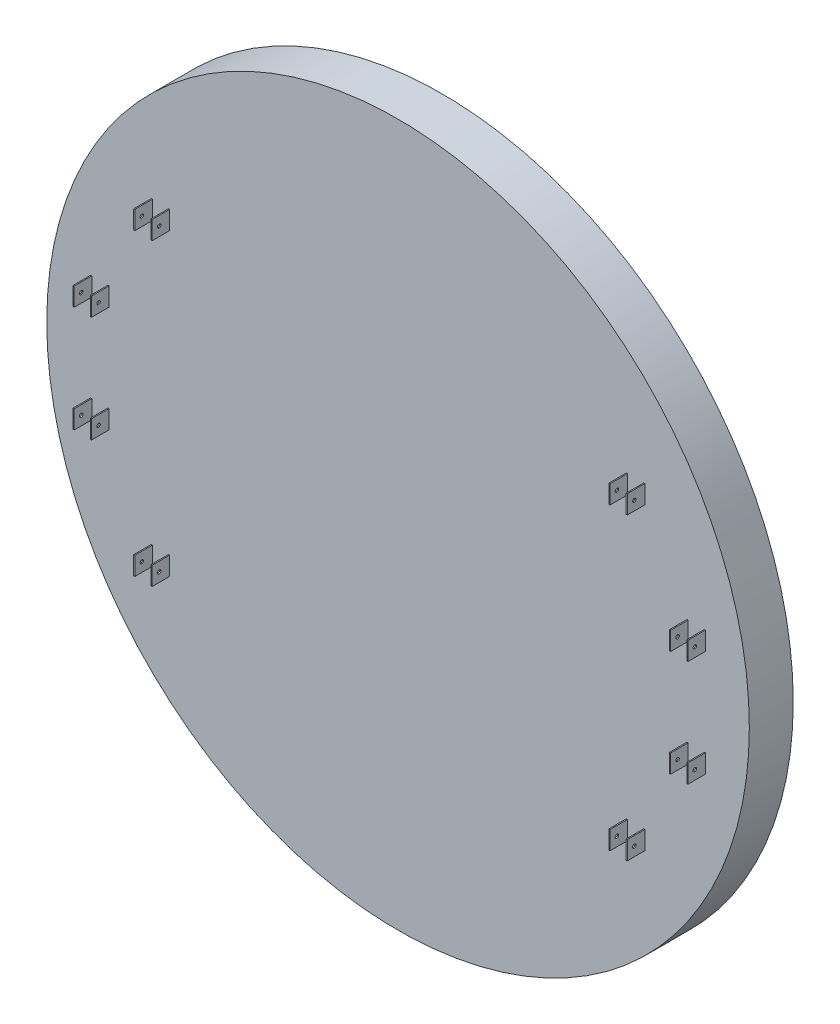
SolidWorks part; units mm, degrees
ref_plane "Front Plane" through (0, 0, 0) normal (0, 0, 1) x (1, 0, 0)
ref_plane "Top Plane" through (0, 0, 0) normal (0, 1, 0) x (1, 0, 0)
ref_plane "Right Plane" through (0, 0, 0) normal (1, 0, 0) x (0, 0, -1)
sketch "Sketch1" plane through (0, 0, 0) normal (0, 0, 1) x (1, 0, 0)
  circle A0 centre (0, 0) radius 400
extrude "Boss-Extrude1" add sketch "Sketch1" along normal blind 50
sketch "Sketch2" plane through (0, 0, 50) normal (0, 0, 1) x (1, 0, 0)
  line L0 (0, 0) -> (400, 0) construction
  line L1 (0, 0) -> (0, 400) construction
  line L2 (350, -50) -> (329, -50)
  line L3 (350, 71) -> (329, 71)
  line L4 (350, 71) -> (350, 50)
  line L5 (350, 50) -> (329, 50)
  line L6 (329, 71) -> (329, 50)
  line L7 (350, -50) -> (350, -71)
  line L8 (329, -50) -> (329, -71)
  line L9 (350, -71) -> (329, -71)
  line L10 (281, -160) -> (281, -181)
  line L11 (281, 160) -> (260, 160)
  line L12 (281, 160) -> (281, 181)
  line L13 (281, 181) -> (260, 181)
  line L14 (260, 160) -> (260, 181)
  line L15 (260, -160) -> (260, -181)
  line L16 (281, -160) -> (260, -160)
  line L17 (281, -181) -> (260, -181)
  line L18 (-281, -181) -> (-260, -181)
  line L19 (-260, -160) -> (-260, -181)
  line L20 (-281, -160) -> (-260, -160)
  line L21 (-281, -160) -> (-281, -181)
  line L22 (-329, -50) -> (-329, -71)
  line L23 (-350, -50) -> (-329, -50)
  line L24 (-350, -50) -> (-350, -71)
  line L25 (-350, -71) -> (-329, -71)
  line L26 (-350, 71) -> (-350, 50)
  line L27 (-350, 71) -> (-329, 71)
  line L28 (-329, 71) -> (-329, 50)
  line L29 (-350, 50) -> (-329, 50)
  line L30 (-281, 160) -> (-260, 160)
  line L31 (-260, 160) -> (-260, 181)
  line L32 (-281, 160) -> (-281, 181)
  line L33 (-281, 181) -> (-260, 181)
  circle A0 centre (0, 0) radius 400 construction
  point P23 (260, -170.5)
  dimension "D1" = 21
  dimension "D2" = 21
  dimension "D3" = 50
  dimension "D4" = 350
  dimension "D6" = 50
  dimension "D7" = 350
  dimension "D8" = 260
  dimension "D9" = 160
  dimension "D10" = 21
  dimension "D11" = 21
  dimension "D12" = 160
  dimension "D13" = 260
  dimension "D5" = 2
extrude "Boss-Extrude2" add sketch "Sketch2" along normal blind 20
sketch "Sketch4" plane through (0, 0, 70) normal (0, 0, 1) x (1, 0, 0)
  line L1 (279.75, 181) -> (261.25, 181)
  line L2 (279.75, 181) -> (279.75, 160)
  line L3 (279.75, 160) -> (261.25, 160)
  line L4 (261.25, 181) -> (261.25, 160)
  line L6 (260, 160) -> (281, 160) construction
  line L11 (260, 181) -> (260, 160) construction
  line L12 (329, 71) -> (329, 50) construction
  line L13 (348.75, 71) -> (330.25, 71)
  line L14 (348.75, 71) -> (348.75, 50)
  line L15 (348.75, 50) -> (330.25, 50)
  line L16 (330.25, 71) -> (330.25, 50)
  line L17 (350, 71) -> (329, 71) construction
  line L19 (350, -50) -> (329, -50) construction
  line L20 (348.75, -50) -> (330.25, -50)
  line L21 (348.75, -50) -> (348.75, -71)
  line L22 (348.75, -71) -> (330.25, -71)
  line L23 (330.25, -50) -> (330.25, -71)
  line L24 (350, -71) -> (350, -50) construction
  line L25 (281, -160) -> (260, -160) construction
  line L26 (279.75, -160) -> (261.25, -160)
  line L27 (279.75, -160) -> (279.75, -181)
  line L28 (279.75, -181) -> (261.25, -181)
  line L29 (261.25, -160) -> (261.25, -181)
  line L30 (281, -181) -> (281, -160) construction
  line L31 (0, 0) -> (0, 414.4663) construction
  line L32 (-261.25, -160) -> (-261.25, -181)
  line L33 (-279.75, -181) -> (-261.25, -181)
  line L34 (-279.75, -160) -> (-279.75, -181)
  line L35 (-279.75, -160) -> (-261.25, -160)
  line L36 (-330.25, -50) -> (-330.25, -71)
  line L37 (-348.75, -71) -> (-330.25, -71)
  line L38 (-348.75, -50) -> (-348.75, -71)
  line L39 (-348.75, -50) -> (-330.25, -50)
  line L40 (-330.25, 71) -> (-330.25, 50)
  line L41 (-348.75, 50) -> (-330.25, 50)
  line L42 (-348.75, 71) -> (-348.75, 50)
  line L43 (-348.75, 71) -> (-330.25, 71)
  line L44 (-261.25, 181) -> (-261.25, 160)
  line L45 (-279.75, 160) -> (-261.25, 160)
  line L46 (-279.75, 181) -> (-279.75, 160)
  line L47 (-279.75, 181) -> (-261.25, 181)
  dimension "D1" = 21
  dimension "D2" = 18.5
  dimension "D3" = 0
  dimension "D4" = 1.25
  dimension "D5" = 1.25
  dimension "D6" = 0
  dimension "D7" = 18.5
  dimension "D8" = 21
  dimension "D9" = 21
  dimension "D10" = 0
  dimension "D11" = 18.5
  dimension "D12" = 1.25
  dimension "D13" = 18.5
  dimension "D14" = 21
  dimension "D15" = 0
  dimension "D16" = 1.25
extrude "Cut-Extrude1" cut sketch "Sketch4" against normal blind 20
sketch "Sketch5" plane through (281, 0, 0) normal (1, 0, 0) x (0, 0, -1)
  line L0 (-70, 160) -> (-70, 181) construction
  line L1 (-70, 50) -> (-70, 71) construction
  line L2 (-70, -71) -> (-70, -50) construction
  line L3 (-70, -181) -> (-70, -160) construction
  circle A0 centre (-62, 170.5) radius 2
  circle A1 centre (-62, 60.5) radius 2
  circle A2 centre (-62, -60.5) radius 2
  circle A3 centre (-62, -170.5) radius 2
  point P12 (-70, 60.5)
  dimension "D1" = 8
  dimension "D2" = 8
  dimension "D3" = 8
  dimension "D4" = 8
extrude "Cut-Extrude2" cut sketch "Sketch5" against normal through all and the other way through all
sketch "Sketch6" plane through (0, 0, 0) normal (0, 0, -1) x (-1, 0, 0)
  line L0 (0, 0) -> (0, 400) construction
  line L5 (0, 0) -> (-346.4102, -200) construction
  line L6 (0, 0) -> (346.4102, -200) construction
  circle A0 centre (0, 0) radius 400 construction
  circle A1 centre (298.6678, -172.4359) radius 4.3801
  circle A2 centre (0, 342.4636) radius 5.4252
  circle A3 centre (-298.6678, -172.4359) radius 8.4214
  circle A4 centre (276.7464, -159.7796) radius 2.8149
  circle A5 centre (-276.7464, -159.7796) radius 5.9419
  circle A6 centre (0, 311.2357) radius 3.1972
  circle A7 centre (263.6416, -152.2135) radius 2.0279
extrude "Cut-Extrude3" cut sketch "Sketch6" against normal blind 10
